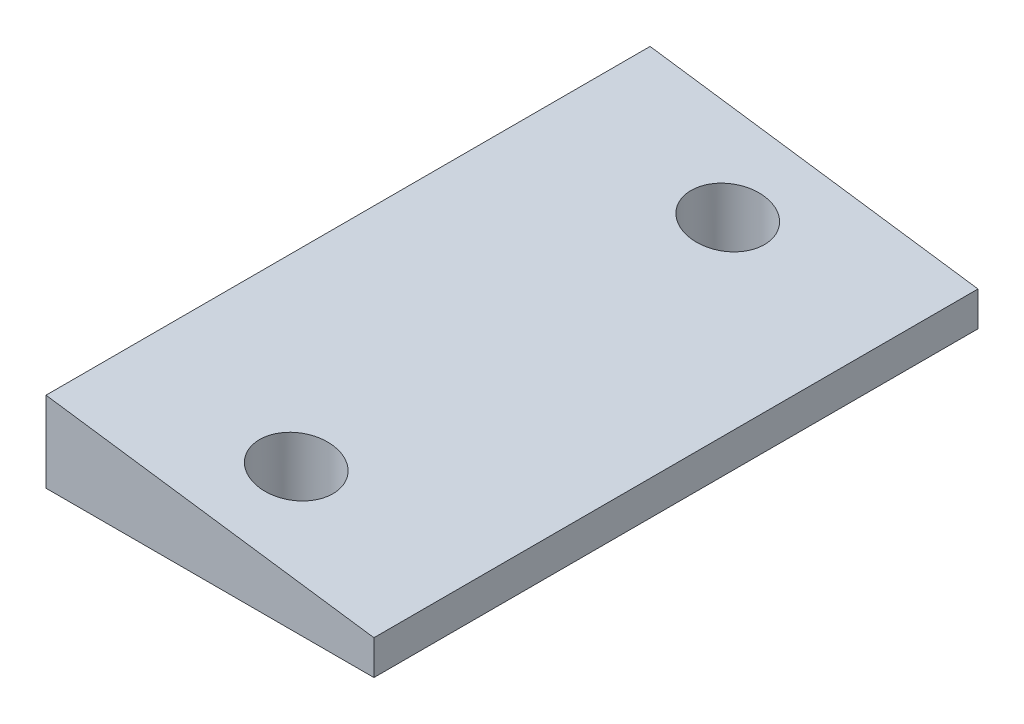
SolidWorks part; units mm, degrees
ref_plane "Płaszczyzna przednia" through (0, 0, 0) normal (0, 0, 1) x (1, 0, 0)
ref_plane "Płaszczyzna górna" through (0, 0, 0) normal (0, 1, 0) x (1, 0, 0)
ref_plane "Płaszczyzna prawa" through (0, 0, 0) normal (1, 0, 0) x (0, 0, -1)
sketch "Szkic1" plane through (0, 0, 0) normal (0, 0, 1) x (1, 0, 0)
  line L0 (-29.0173, 0) -> (30.2457, 0) construction
  line L1 (0, 20.0247) -> (0, -27.335) construction
  line L2 (-16.5582, 5.2371) -> (-16.5582, -4.1034)
  line L3 (-16.5582, -4.1034) -> (21.4418, -4.1034)
  line L4 (21.4418, -4.1034) -> (21.4418, -0.1034)
  line L6 (-16.5582, -28.29) -> (-16.5582, 30.6374) construction
  line L7 (-19.4953, -15.6612) -> (-14.6544, 18.7831) construction
  line L8 (-16.5582, 5.2371) -> (21.4418, -0.1034)
  dimension "D1" = 38
  dimension "D2" = 8
  dimension "D3" = 4
extrude "Dodanie-wyciągnięcie1" add sketch "Szkic1" along normal blind 70
ref_plane "Płaszczyzna1" through (0, 5.2371, 0) normal (0, -1, 0) x (-1, 0, 0)
sketch "Szkic2" plane through (0, 5.2371, 0) normal (0, -1, 0) x (-1, 0, 0)
  line L0 (-2.4418, -71.2527) -> (-2.4418, 2.237) construction
  line L1 (21.508, -35) -> (-18.9278, -35) construction
  circle A0 centre (-2.4418, -60) radius 4.25
  circle A1 centre (-2.4418, -10) radius 4.25
  dimension "D1" = 8.5
  dimension "D2" = 25
  dimension "D3" = 8.5
  dimension "D4" = 25
extrude "Wytnij-wyciągnięcie1" cut sketch "Szkic2" along normal blind 10
